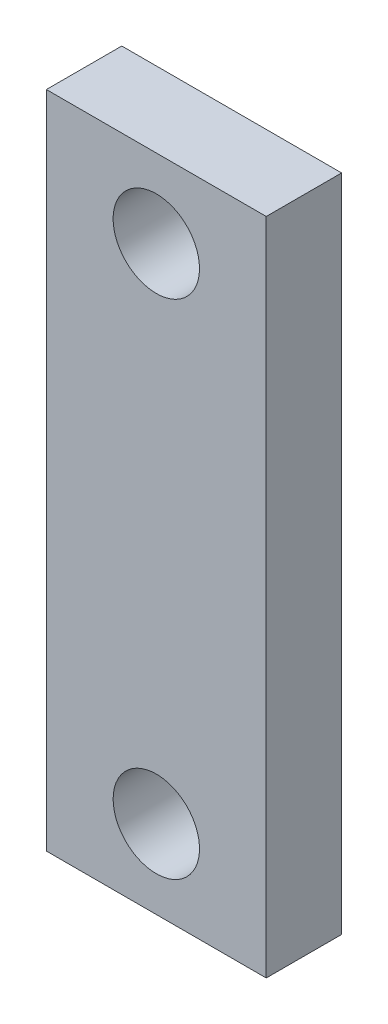
SolidWorks part; units mm, degrees
ref_plane "前视基准面" through (0, 0, 0) normal (0, 0, 1) x (1, 0, 0)
ref_plane "上视基准面" through (0, 0, 0) normal (0, 1, 0) x (1, 0, 0)
ref_plane "右视基准面" through (0, 0, 0) normal (1, 0, 0) x (0, 0, -1)
other "Configuration Table"
sketch "草图1" plane through (0, 0, 0) normal (0, 0, 1) x (1, 0, 0)
  line L0 (-7, 0) -> (7, 0) construction
  line L1 (-7, 21) -> (7, 21)
  line L2 (-7, 21) -> (-7, -21)
  line L3 (-7, -21) -> (7, -21)
  line L4 (7, 21) -> (7, -21)
  line L5 (-7, 21) -> (7, -21) construction
  line L6 (-7, -21) -> (7, 21) construction
  line L7 (0, 21) -> (0, -21) construction
  circle A0 centre (0, 16) radius 2.75
  circle A1 centre (0, -16) radius 2.75
  point P0 (0, 0)
  dimension "D3" = 32
  dimension "D4" = 5.5
  dimension "D1" = 14
  dimension "D2" = 42
extrude "凸台-拉伸1" add sketch "草图1" along normal blind 4.8
